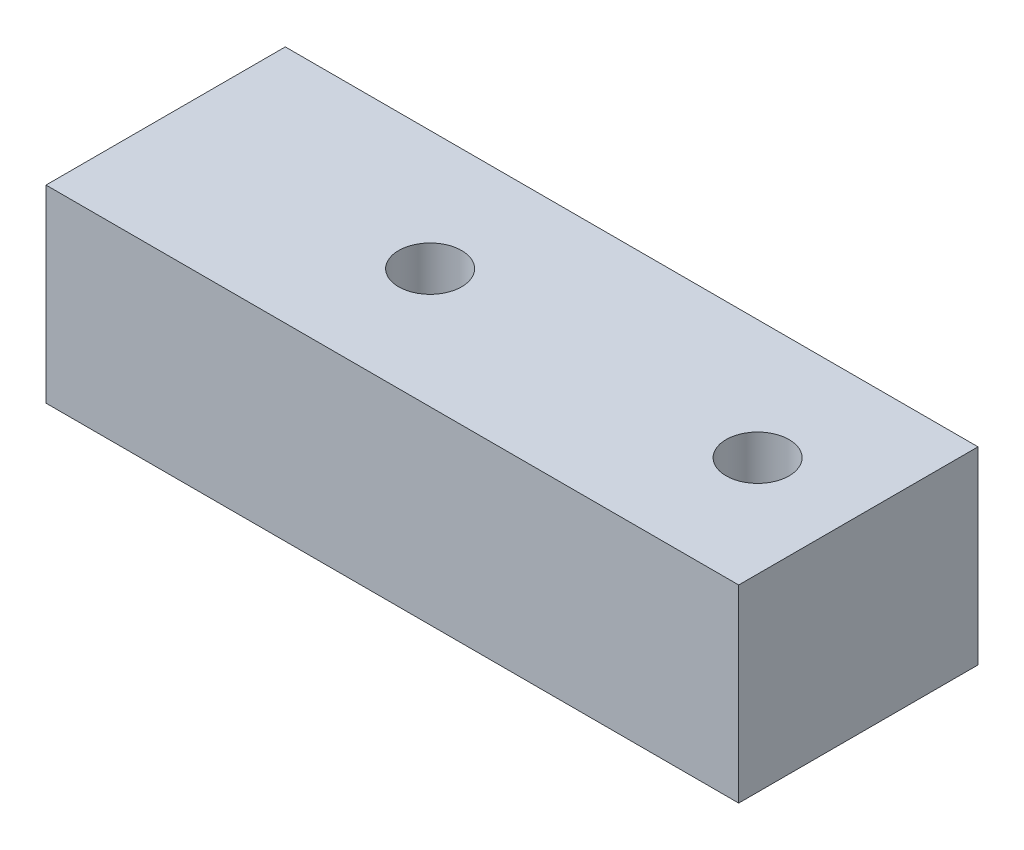
SolidWorks part; units mm, degrees
ref_plane "Front Plane" through (0, 0, 0) normal (0, 0, 1) x (1, 0, 0)
ref_plane "Top Plane" through (0, 0, 0) normal (0, 1, 0) x (1, 0, 0)
ref_plane "Right Plane" through (0, 0, 0) normal (1, 0, 0) x (0, 0, -1)
sketch "Sketch1" plane through (0, 0, 0) normal (0, 1, 0) x (1, 0, 0)
  line L1 (-22.8263, 11.9762) -> (32.1737, 11.9762)
  line L2 (-22.8263, 11.9762) -> (-22.8263, -7.0238)
  line L3 (-22.8263, -7.0238) -> (32.1737, -7.0238)
  line L4 (32.1737, 11.9762) -> (32.1737, -7.0238)
  dimension "D1" = 55
  dimension "D2" = 19
extrude "Boss-Extrude1" add sketch "Sketch1" along normal blind 15
sketch "Sketch2" plane through (0, 15, 0) normal (0, 1, 0) x (1, 0, 0)
  line L0 (-22.8263, 2.4762) -> (32.1737, 2.4762) construction
  line L1 (-22.8263, 11.9762) -> (-22.8263, -7.0238) construction
  line L2 (32.1737, -7.0238) -> (32.1737, 11.9762) construction
  circle A0 centre (24.1737, 2.4762) radius 2.5
  circle A1 centre (-1.8263, 2.4762) radius 2.5
  dimension "D3" = 5
  dimension "D1" = 8
  dimension "D2" = 34
extrude "Cut-Extrude1" cut sketch "Sketch2" against normal through all
